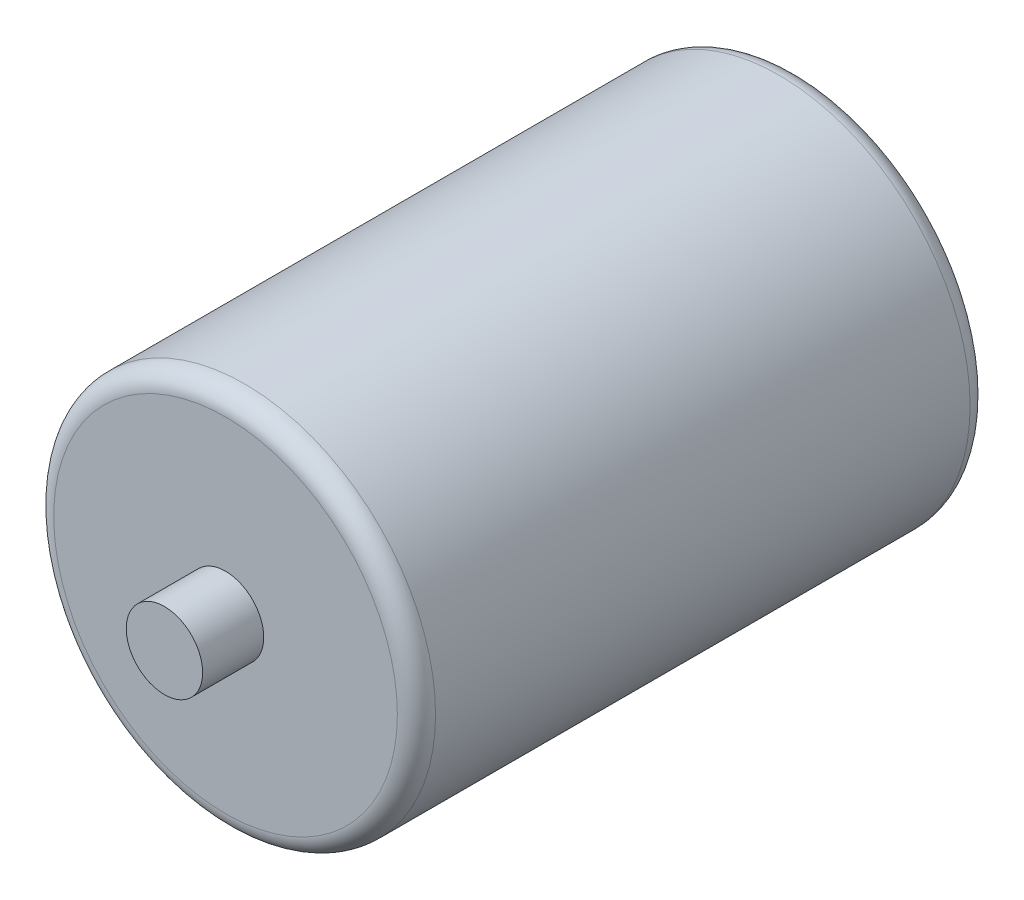
SolidWorks part; units mm, degrees
ref_plane "Front Plane" through (0, 0, 0) normal (0, 0, 1) x (1, 0, 0)
ref_plane "Top Plane" through (0, 0, 0) normal (0, 1, 0) x (1, 0, 0)
ref_plane "Right Plane" through (0, 0, 0) normal (1, 0, 0) x (0, 0, -1)
sketch "Sketch2" plane through (0, 0, 0) normal (0, 0, 1) x (1, 0, 0)
  circle A0 centre (0, 0) radius 1270
  dimension "D1" = 2540
extrude "Boss-Extrude1" add sketch "Sketch2" along normal blind 3810 contours A0
sketch "Sketch3" plane through (0, 0, 3810) normal (0, 0, 1) x (1, 0, 0)
  circle A0 centre (0, 0) radius 254
  dimension "D1" = 508
extrude "Boss-Extrude2" add sketch "Sketch3" along normal blind 406.4
sketch "Sketch4" plane through (0, 0, 0) normal (0, 0, -1) x (-1, 0, 0)
  circle A0 centre (0, 0) radius 254
  dimension "D1" = 508
extrude "Boss-Extrude3" add sketch "Sketch4" along normal blind 406.4
fillet "Fillet1" radius 127 2 edges at (1270, 0, 0) (1270, 0, 3810)
